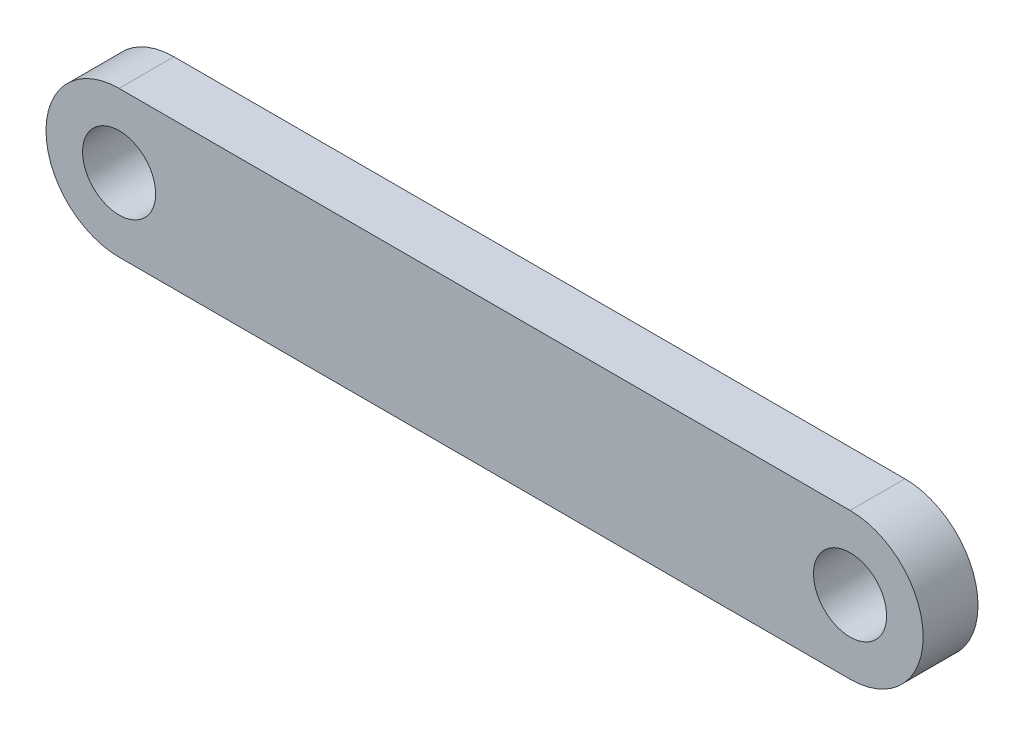
SolidWorks part; units mm, degrees
ref_plane "Front Plane" through (0, 0, 0) normal (0, 0, 1) x (1, 0, 0)
ref_plane "Top Plane" through (0, 0, 0) normal (0, 1, 0) x (1, 0, 0)
ref_plane "Right Plane" through (0, 0, 0) normal (1, 0, 0) x (0, 0, -1)
sketch "Sketch1" plane through (0, 0, 0) normal (0, 0, 1) x (1, 0, 0)
  line L0 (-25.4, 0) -> (25.4, 0) construction
  line L1 (-25.4, 5.08) -> (25.4, 5.08)
  line L2 (-25.4, -5.08) -> (25.4, -5.08)
  arc A0 (-25.4, 5.08) -> (-25.4, -5.08) centre (-25.4, 0) ccw
  arc A1 (25.4, -5.08) -> (25.4, 5.08) centre (25.4, 0) ccw
  circle A2 centre (-25.4, 0) radius 2.54
  circle A3 centre (25.4, 0) radius 2.54
  point P2 (0, 0)
  dimension "D3" = 5.08
  dimension "D1" = 50.8
  dimension "D2" = 10.16
extrude "Boss-Extrude1" add sketch "Sketch1" along normal blind 3.81
